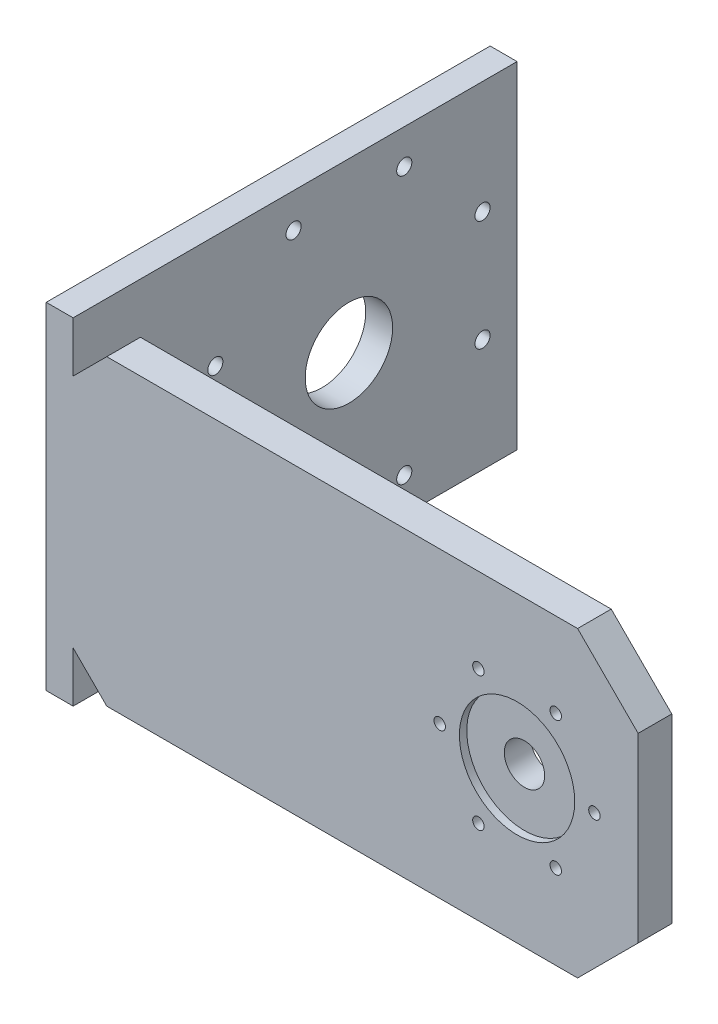
SolidWorks part; units mm, degrees
ref_plane "Front Plane" through (0, 0, 0) normal (0, 0, 1) x (1, 0, 0)
ref_plane "Top Plane" through (0, 0, 0) normal (0, 1, 0) x (1, 0, 0)
ref_plane "Right Plane" through (0, 0, 0) normal (1, 0, 0) x (0, 0, -1)
ref_plane "PL_Top_Plate_base" through (0, 0, 72) normal (0, 0, 1) x (1, 0, 0)
sketch "SK_Top_Plate" plane through (0, 0, 72) normal (0, 0, 1) x (1, 0, 0)
  line L0 (-122, 45) -> (18, 45)
  line L1 (18, 45) -> (36, 27)
  line L2 (36, 27) -> (36, -27)
  line L3 (36, -27) -> (18, -45)
  line L4 (18, -45) -> (-122, -45)
  line L5 (-122, -45) -> (-140, -27)
  line L6 (-140, -27) -> (-140, 27)
  line L7 (-140, 27) -> (-122, 45)
  circle A0 centre (23, 0) radius 1.7
  circle A1 centre (11.5, -19.9186) radius 1.7
  circle A2 centre (-11.5, -19.9186) radius 1.7
  circle A3 centre (-23, 0) radius 1.7
  circle A4 centre (-11.5, 19.9186) radius 1.7
  circle A5 centre (11.5, 19.9186) radius 1.7
  circle A6 centre (0, 0) radius 6
  dimension "D17_SK_Top_Plate" = 3.4
  dimension "D19_SK_Top_Plate" = 3.4
  dimension "D22_SK_Top_Plate" = 3.4
  dimension "D25_SK_Top_Plate" = 3.4
  dimension "D27_SK_Top_Plate" = 3.4
  dimension "D30_SK_Top_Plate" = 3.4
  dimension "D33_SK_Top_Plate" = 12
  dimension "P1" = 122
  dimension "P2" = 45
  dimension "P3" = 18
  dimension "P4" = 45
  dimension "P5" = 36
  dimension "P6" = 27
  dimension "P7" = 36
  dimension "P8" = 27
  dimension "P9" = 18
  dimension "P10" = 45
  dimension "P11" = 122
  dimension "P12" = 45
  dimension "P13" = 140
  dimension "P14" = 27
  dimension "P15" = 140
  dimension "P16" = 27
  dimension "P18" = 23
  dimension "P20" = 11.5
  dimension "P21" = 19.9186
  dimension "P23" = 11.5
  dimension "P24" = 19.9186
  dimension "P26" = 23
  dimension "P28" = 11.5
  dimension "P29" = 19.9186
  dimension "P31" = 11.5
  dimension "P32" = 19.9186
extrude "Top_Plate" add sketch "SK_Top_Plate" along normal blind 10
ref_plane "PL_Yaw_Pilot_Recess_base" through (0, 0, 82) normal (0, 0, 1) x (1, 0, 0)
sketch "SK_Yaw_Pilot_Recess" plane through (0, 0, 82) normal (0, 0, 1) x (1, 0, 0)
  circle A0 centre (0, 0) radius 17.15
  dimension "D1_SK_Yaw_Pilot_Recess" = 34.3
extrude "Yaw_Pilot_Recess" cut sketch "SK_Yaw_Pilot_Recess" against normal blind 2.2
ref_plane "PL_Back_Plate_base" through (-140, 0, 0) normal (1, 0, 0) x (0, 0, -1)
sketch "SK_Back_Plate" plane through (-140, 0, 0) normal (1, 0, 0) x (0, 0, -1)
  line L0 (50, 50) -> (50, -50)
  line L1 (50, -50) -> (-82, -50)
  line L2 (-82, -50) -> (-82, 50)
  line L3 (-82, 50) -> (50, 50)
  circle A0 centre (39.7268, -16.4554) radius 2.25
  circle A1 centre (16.4554, -39.7268) radius 2.25
  circle A2 centre (-16.4554, -39.7268) radius 2.25
  circle A3 centre (-39.7268, -16.4554) radius 2.25
  circle A4 centre (-39.7268, 16.4554) radius 2.25
  circle A5 centre (-16.4554, 39.7268) radius 2.25
  circle A6 centre (16.4554, 39.7268) radius 2.25
  circle A7 centre (39.7268, 16.4554) radius 2.25
  circle A8 centre (0, 0) radius 13
  dimension "D9_SK_Back_Plate" = 4.5
  dimension "D12_SK_Back_Plate" = 4.5
  dimension "D15_SK_Back_Plate" = 4.5
  dimension "D18_SK_Back_Plate" = 4.5
  dimension "D21_SK_Back_Plate" = 4.5
  dimension "D24_SK_Back_Plate" = 4.5
  dimension "D27_SK_Back_Plate" = 4.5
  dimension "D30_SK_Back_Plate" = 4.5
  dimension "D33_SK_Back_Plate" = 26
  dimension "P1" = 50
  dimension "P2" = 50
  dimension "P3" = 50
  dimension "P4" = 50
  dimension "P5" = 82
  dimension "P6" = 50
  dimension "P7" = 82
  dimension "P8" = 50
  dimension "P10" = 39.7268
  dimension "P11" = 16.4554
  dimension "P13" = 16.4554
  dimension "P14" = 39.7268
  dimension "P16" = 16.4554
  dimension "P17" = 39.7268
  dimension "P19" = 39.7268
  dimension "P20" = 16.4554
  dimension "P22" = 39.7268
  dimension "P23" = 16.4554
  dimension "P25" = 16.4554
  dimension "P26" = 39.7268
  dimension "P28" = 16.4554
  dimension "P29" = 39.7268
  dimension "P31" = 39.7268
  dimension "P32" = 16.4554
extrude "Back_Plate" add sketch "SK_Back_Plate" along normal blind 8
ref_plane "PL_Rib_base" through (0, -4, 0) normal (0, 1, 0) x (1, 0, 0)
sketch "SK_Rib" plane through (0, -4, 0) normal (0, 1, 0) x (1, 0, 0)
  line L0 (-140, -52) -> (-30, -72)
  line L1 (-30, -72) -> (-140, -72)
  line L2 (-140, -72) -> (-140, -52)
  dimension "P1" = 140
  dimension "P2" = 52
  dimension "P3" = 30
  dimension "P4" = 72
  dimension "P5" = 140
  dimension "P6" = 72
extrude "Rib" add sketch "SK_Rib" along normal blind 8
equation "\"Yaw_face_z\" = 82"
equation "\"Roll_rear_x\" = -132"
